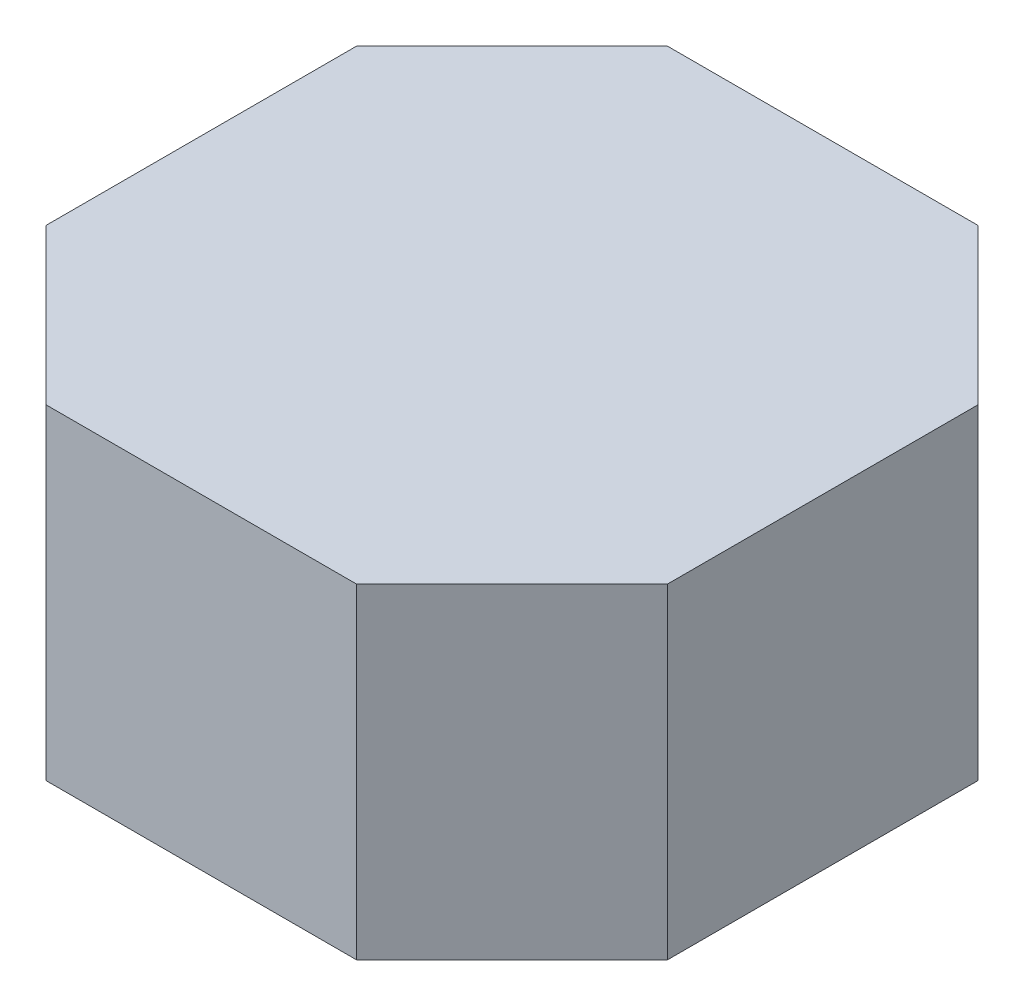
SolidWorks part; units mm, degrees
ref_plane "Front Plane" through (0, 0, 0) normal (0, 0, 1) x (1, 0, 0)
ref_plane "Top Plane" through (0, 0, 0) normal (0, 1, 0) x (1, 0, 0)
ref_plane "Right Plane" through (0, 0, 0) normal (1, 0, 0) x (0, 0, -1)
sketch "Sketch1" plane through (0, 0, 0) normal (0, 1, 0) x (1, 0, 0)
  line L1 (-21, 21) -> (21, 21)
  line L2 (-21, 21) -> (-21, -21)
  line L3 (-21, -21) -> (21, -21)
  line L4 (21, 21) -> (21, -21)
  line L5 (-21, 21) -> (21, -21) construction
  line L6 (-21, -21) -> (21, 21) construction
  point P0 (0, 0)
  dimension "D1" = 42
  dimension "D2" = 42
extrude "Nema 17" add sketch "Sketch1" along normal blind 22
chamfer "Chamfer1" distance 10.5 angle 45 4 edges at (-21, 11, -21) (21, 11, -21) (21, 11, 21) (-21, 11, 21)
